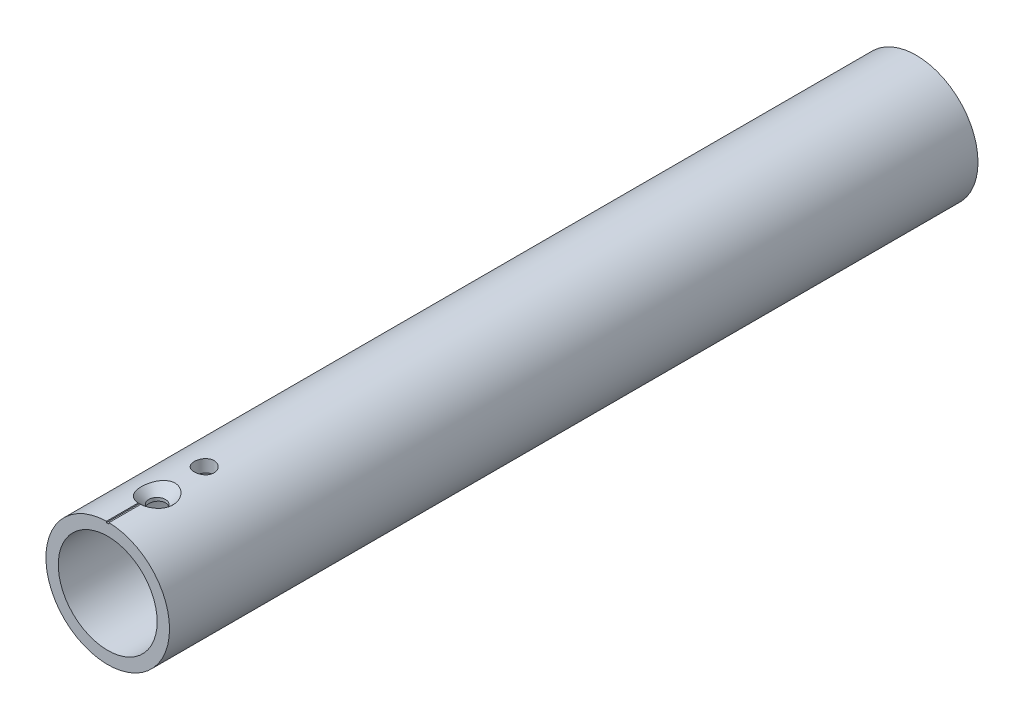
SolidWorks part; units mm, degrees
ref_plane "Front Plane" through (0, 0, 0) normal (0, 0, 1) x (1, 0, 0)
ref_plane "Top Plane" through (0, 0, 0) normal (0, 1, 0) x (1, 0, 0)
ref_plane "Right Plane" through (0, 0, 0) normal (1, 0, 0) x (0, 0, -1)
sketch "Sketch1" plane through (0, 0, 0) normal (0, 0, 1) x (1, 0, 0)
  circle A2 centre (0, 0) radius 10
  circle A3 centre (0, 0) radius 12.5
  dimension "D1" = 25
  dimension "D2" = 20
extrude "Boss-Extrude1" add sketch "Sketch1" against normal blind 163.5
ref_plane "Plane1" through (0, 12.5, 0) normal (0, 1, 0) x (0, 0, 1)
sketch "Sketch4" plane through (0, 12.5, 0) normal (0, 1, 0) x (0, 0, 1)
  line L0 (13.75, 0) -> (-13.75, 0) construction
  point P0 (-10, 0)
  dimension "D1" = 10
hole_wizard "CSK for M3 SFHCS1" positions "Sketch4" profile "Sketch5" countersink size "M3" standard "ANSI Metric"
sketch "Sketch5" plane through (0, 12.5, -10) normal (1, 0, 0) x (0, 0, 1)
  line L0 (0, 0) -> (0, 11.0215)
  line L1 (0, 11.0215) -> (1.7, 10)
  line L2 (1.7, 10) -> (1.7, 1.91)
  line L3 (1.7, 1.91) -> (3.61, 0)
  line L5 (3.61, 0) -> (0, 0)
  line L6 (-1.7, 1.91) -> (-3.61, 0) construction
  line L10 (0, 11.0215) -> (-1.7, 10) construction
  line L11 (0, -6.35) -> (0, 107.95) construction
  dimension "Hole Dia." = 3.4
  dimension "Hole Depth" = 10
  dimension "Near C'Sink Dia." = 7.22
  dimension "Near C'Sink Angle" = 90
  dimension "Drill Angle" = 118
sketch "Sketch6" plane through (0, 12.5, 0) normal (0, 1, 0) x (0, 0, 1)
  line L0 (-19.5, 0) -> (0, 0) construction
  point P0 (-19.5, 0)
  dimension "D1" = 19.5
hole_wizard "Ø4.0mm Dowel Hole1" positions "Sketch6" profile "Sketch7" hole size "Ø4.0" standard "ANSI Metric" end condition through all
sketch "Sketch7" plane through (0, 12.5, -19.5) normal (1, 0, 0) x (0, 0, 1)
  line L0 (0, 0) -> (0, 25)
  line L1 (0, 25) -> (2, 25)
  line L2 (2, 25) -> (2, 0)
  line L5 (2, 0) -> (0, 0)
  line L11 (0, -6.35) -> (0, 107.95) construction
  dimension "Thru Hole Dia." = 4
  dimension "Thru Hole Depth" = 25
sketch "Sketch8" plane through (0, 12.5, 0) normal (0, 1, 0) x (0, 0, 1)
  line L0 (0, 0.25) -> (-10, 0.25)
  line L1 (-10, 0.25) -> (-10, -0.25)
  line L2 (-10, -0.25) -> (0, -0.25)
  line L3 (0, -0.25) -> (0, 0.25)
  line L4 (0, 0) -> (-10, 0) construction
  line L5 (13.75, 0) -> (-13.75, 0) construction
  line L6 (0, -13.75) -> (0, 13.75) construction
  point P10 (0, 0)
  dimension "D1" = 0.25
  dimension "D2" = 0.25
extrude "Cut-Extrude1" cut sketch "Sketch8" against normal blind 0.25
